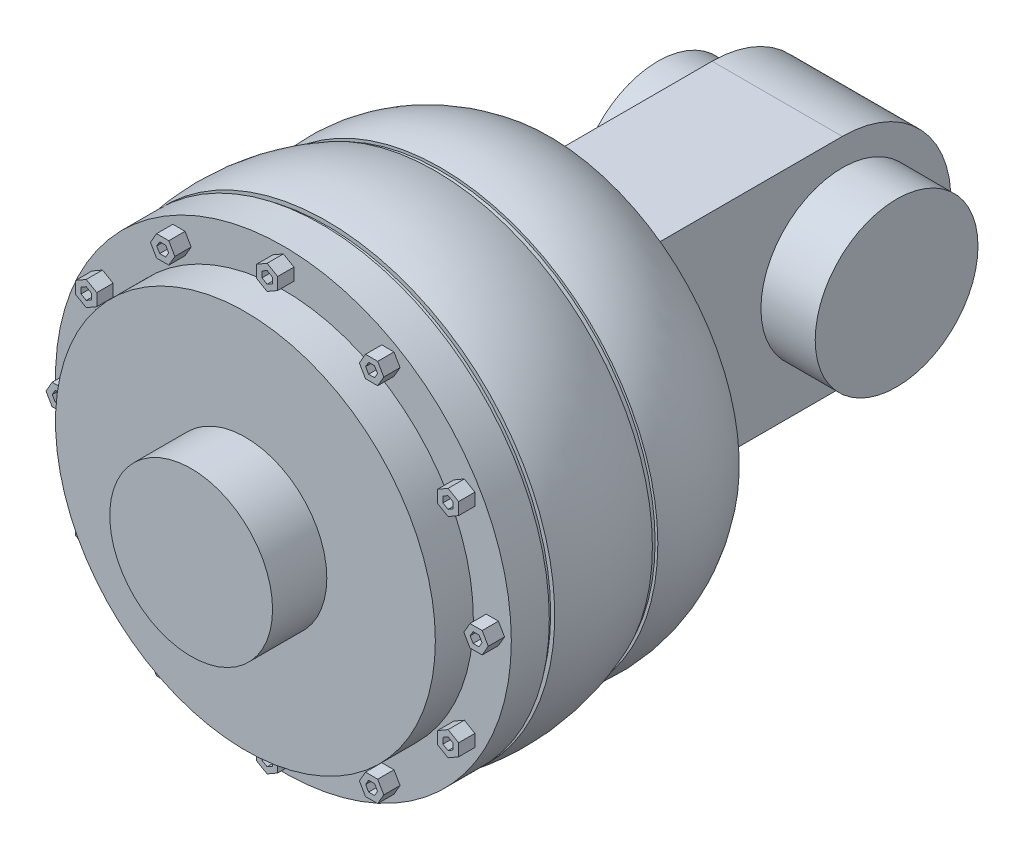
SolidWorks part; units mm, degrees
ref_plane "Front Plane" through (0, 0, 0) normal (0, 0, 1) x (1, 0, 0)
ref_plane "Top Plane" through (0, 0, 0) normal (0, 1, 0) x (1, 0, 0)
ref_plane "Right Plane" through (0, 0, 0) normal (1, 0, 0) x (0, 0, -1)
sketch "Sketch2" plane through (0, 0, 0) normal (0, 1, 0) x (1, 0, 0)
  line L0 (-35, 0) -> (0, 0)
  line L1 (0, 0) -> (0, -20)
  line L2 (0, -20) -> (-40, -20)
  arc A0 (-40, -20) -> (-35, 0) centre (-15.404, -15.524) cw
  dimension "D4" = 25
  dimension "D1" = 35
  dimension "D2" = 20
  dimension "D3" = 40
revolve "Revolve1" add sketch "Sketch2" angle 360 about L1
sketch "Sketch3" plane through (0, 0, 20) normal (0, 0, 1) x (1, 0, 0)
  circle A0 centre (0, 0) radius 39.5
  dimension "D1" = 79
extrude "Boss-Extrude1" add sketch "Sketch3" along normal blind 1
sketch "Sketch4" plane through (0, 0, 0) normal (0, 1, 0) x (1, 0, 0)
  line L0 (-40, -21) -> (0, -21)
  line L1 (-39.5, -21) -> (39.5, -21) construction
  line L2 (0, -21) -> (0, -41)
  line L3 (0, -41) -> (-42, -41)
  arc A0 (-42, -41) -> (-40, -21) centre (-5.5677, -34.5432) cw
  dimension "D4" = 37
  dimension "D1" = 20
  dimension "D2" = 40
  dimension "D3" = 42
revolve "Revolve2" add sketch "Sketch4" angle 360 about L2
sketch "Sketch5" plane through (0, 0, 41) normal (0, 0, 1) x (1, 0, 0)
  circle A0 centre (0, 0) radius 41.25
  dimension "D1" = 82.5
extrude "Boss-Extrude2" add sketch "Sketch5" along normal blind 1
sketch "Sketch6" plane through (0, 0, 42) normal (0, 0, 1) x (1, 0, 0)
  circle A0 centre (0, 0) radius 42
  dimension "D1" = 84
extrude "Boss-Extrude3" add sketch "Sketch6" along normal blind 7
sketch "Sketch7" plane through (0, 0, 49) normal (0, 0, 1) x (1, 0, 0)
  circle A0 centre (0, 0) radius 35
  dimension "D1" = 70
extrude "Boss-Extrude4" add sketch "Sketch7" along normal blind 7
sketch "Sketch8" plane through (0, 0, 49) normal (0, 0, 1) x (1, 0, 0)
  line L0 (35, 0) -> (42, 0) construction
  line L1 (39.0476, 0.9486) -> (37.9524, 0.9486)
  line L2 (36.25, 0) -> (37.375, -1.9486)
  line L3 (37.375, -1.9486) -> (39.625, -1.9486)
  line L4 (39.625, -1.9486) -> (40.75, 0)
  line L5 (40.75, 0) -> (39.625, 1.9486)
  line L6 (39.625, 1.9486) -> (37.375, 1.9486)
  line L7 (37.375, 1.9486) -> (36.25, 0)
  line L8 (37.9524, 0.9486) -> (37.4047, 0)
  line L9 (37.4047, 0) -> (37.9524, -0.9486)
  line L10 (37.9524, -0.9486) -> (39.0476, -0.9486)
  line L11 (39.0476, -0.9486) -> (39.5953, 0)
  line L12 (39.5953, 0) -> (39.0476, 0.9486)
  circle A0 centre (0, 0) radius 35 construction
  circle A1 centre (0, 0) radius 42 construction
  circle A2 centre (38.5, 0) radius 1.9486 construction
  dimension "D1" = 4.5
  dimension "D2" = 1
extrude "Boss-Extrude5" add sketch "Sketch8" along normal blind 3
pattern_circular "CirPattern2" count 12 over 360 about axis through (0, 0, 0) along (0, 0, 1) of "Boss-Extrude5"
sketch "Sketch9" plane through (0, 0, 56) normal (0, 0, 1) x (1, 0, 0)
  circle A0 centre (0, 0) radius 15
  dimension "D1" = 30
extrude "Boss-Extrude6" add sketch "Sketch9" along normal blind 10
sketch "Sketch10" plane through (0, 0, 0) normal (0, 0, -1) x (-1, 0, 0)
  line L1 (12, -20) -> (-12, -20)
  line L2 (12, -20) -> (12, 20)
  line L3 (12, 20) -> (-12, 20)
  line L4 (-12, -20) -> (-12, 20)
  line L5 (12, -20) -> (-12, 20) construction
  line L6 (12, 20) -> (-12, -20) construction
  point P0 (0, 0)
  dimension "D1" = 24
  dimension "D2" = 40
extrude "Boss-Extrude7" add sketch "Sketch10" along normal blind 42
sketch "Sketch11" plane through (12, 0, 0) normal (1, 0, 0) x (0, 0, -1)
  line L0 (42, 20) -> (42, -20) construction
  line L1 (42, 20) -> (42, -20)
  arc A0 (42, -20) -> (42, 20) centre (42, 0) ccw
extrude "Boss-Extrude8" add sketch "Sketch11" against normal blind 24
sketch "Sketch12" plane through (12, 0, 0) normal (1, 0, 0) x (0, 0, -1)
  circle A0 centre (42, 0) radius 15
  dimension "D1" = 30
extrude "Boss-Extrude9" add sketch "Sketch12" along normal blind 10
sketch "Sketch13" plane through (-12, 0, 0) normal (-1, 0, 0) x (0, 0, 1)
  circle A0 centre (-42, 0) radius 15
  dimension "D1" = 30
extrude "Boss-Extrude10" add sketch "Sketch13" along normal blind 10
